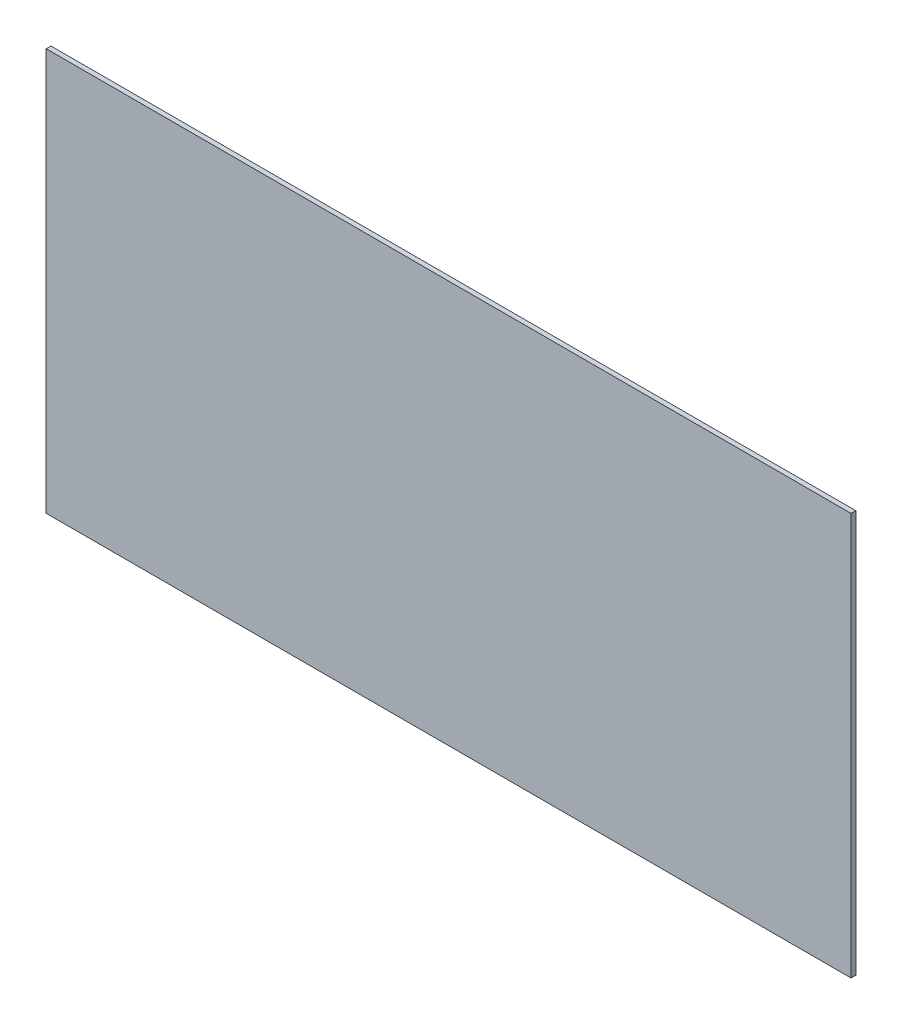
SolidWorks part; units mm, degrees
ref_plane "Alzado" through (0, 0, 0) normal (0, 0, 1) x (1, 0, 0)
ref_plane "Planta" through (0, 0, 0) normal (0, 1, 0) x (1, 0, 0)
ref_plane "Vista lateral" through (0, 0, 0) normal (1, 0, 0) x (0, 0, -1)
sketch "Sketch1" plane through (0, 0, 0) normal (0, 0, 1) x (1, 0, 0)
  line L1 (-170, -85) -> (170, -85)
  line L2 (-170, -85) -> (-170, 85)
  line L3 (-170, 85) -> (170, 85)
  line L4 (170, -85) -> (170, 85)
  line L5 (-170, -85) -> (170, 85) construction
  line L6 (-170, 85) -> (170, -85) construction
  point P0 (0, 0)
  dimension "D1" = 340
  dimension "D2" = 170
extrude "Boss-Extrude1" add sketch "Sketch1" along normal blind 2
